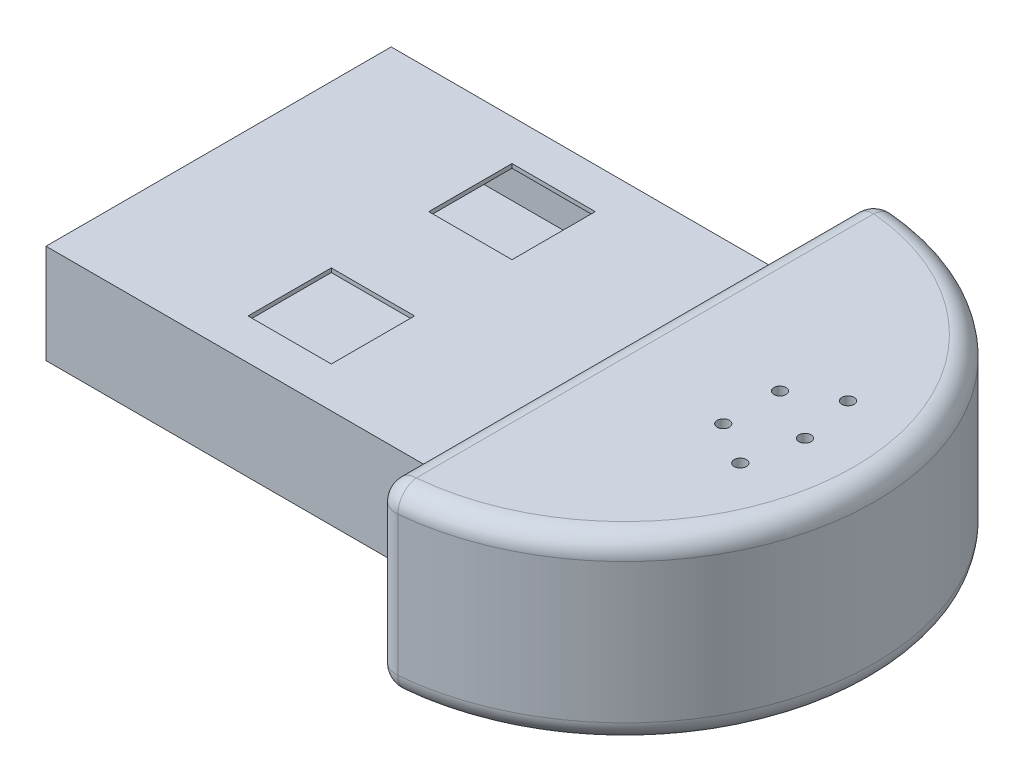
SolidWorks part; units mm, degrees
ref_plane "Front Plane" through (0, 0, 0) normal (0, 0, 1) x (1, 0, 0)
ref_plane "Top Plane" through (0, 0, 0) normal (0, 1, 0) x (1, 0, 0)
ref_plane "Right Plane" through (0, 0, 0) normal (1, 0, 0) x (0, 0, -1)
sketch "Sketch1" plane through (0, 0, 0) normal (0, 1, 0) x (1, 0, 0)
  line L0 (5, 6.1543) -> (5, 4.25)
  line L1 (-5, 4.25) -> (5, 4.25)
  line L2 (-5, 4.25) -> (-5, -4.25)
  line L3 (-5, -4.25) -> (5, -4.25)
  line L5 (-5, 4.25) -> (5, -4.25) construction
  line L6 (-5, -4.25) -> (5, 4.25) construction
  line L7 (5, -4.25) -> (5, -6.1543)
  arc A0 (5, -6.1543) -> (5, 6.1543) centre (5, 0) ccw
  point P0 (0, 0)
  dimension "D1" = 8.5
  dimension "D2" = 10
extrude "Boss-Extrude1" add sketch "Sketch1" along normal blind 2.44
sketch "Sketch2" plane through (0, 2.44, 0) normal (0, 1, 0) x (1, 0, 0)
  line L0 (5, 4.25) -> (5, -4.25) construction
  line L1 (5, 6.1543) -> (5, -6.1543)
  arc A0 (5, -6.1543) -> (5, 6.1543) centre (5, 0) ccw
extrude "Boss-Extrude2" add sketch "Sketch2" along normal blind 1
sketch "Sketch3" plane through (0, 0, 0) normal (0, -1, 0) x (1, 0, 0)
  line L0 (5, 6.1543) -> (5, -6.1543)
  arc A0 (5, -6.1543) -> (5, 6.1543) centre (5, 0) ccw
extrude "Boss-Extrude3" add sketch "Sketch3" along normal blind 1
sketch "Sketch4" plane through (-5, 0, 0) normal (-1, 0, 0) x (0, 0, 1)
  line L0 (0, 2.44) -> (0, 0) construction
  line L1 (-4.25, 2.44) -> (4.25, 2.44) construction
  line L2 (-4.25, 1.22) -> (4.25, 1.22) construction
  line L3 (-4.25, 2.44) -> (-4.25, 0) construction
  line L4 (4.25, 2.44) -> (4.25, 0) construction
  line L5 (-4.25, 2.44) -> (4.25, 2.44) construction
  line L6 (-4.15, 2.34) -> (4.15, 2.34)
  line L7 (-4.15, 2.34) -> (-4.15, 0.75)
  line L8 (-4.15, 0.75) -> (4.15, 0.75)
  line L9 (4.15, 2.34) -> (4.15, 0.75)
  line L10 (4.25, 0) -> (-4.25, 0) construction
  dimension "D1" = 0.1
  dimension "D2" = 0.1
  dimension "D3" = 0.1
  dimension "D4" = 0.75
extrude "Cut-Extrude1" cut sketch "Sketch4" against normal blind 10
fillet "Fillet1" radius 0.5 6 edges at (5, -1, 0) (5, 3.44, 0) (5, 1.22, 6.1543) (5, 1.22, -6.1543) (11.1543, -1, 0) (11.1543, 3.44, 0)
sketch "Sketch5" plane through (0, 3.44, 0) normal (0, 1, 0) x (1, 0, 0)
  line L0 (5.5, 5.6322) -> (5.5, -5.6322) construction
  line L1 (5.5, 0) -> (10.6543, 0) construction
  arc A0 (5.5, -5.6322) -> (5.5, 5.6322) centre (5, 0) ccw construction
  circle A1 centre (9.1722, 1.326) radius 0.15
  circle A2 centre (8.1255, 0.698) radius 0.15
  circle A3 centre (9.4397, 0) radius 0.15
  circle A4 centre (9.1722, -1.326) radius 0.15
  circle A5 centre (8.1255, -0.698) radius 0.15
  dimension "D1" = 0.3
extrude "Cut-Extrude2" cut sketch "Sketch5" against normal blind 0.5
sketch "Sketch6" plane through (0, 2.44, 0) normal (0, 1, 0) x (1, 0, 0)
  line L0 (-5, 0) -> (5, 0) construction
  line L1 (-5, 4.25) -> (-5, -4.25) construction
  line L2 (5, 4.25) -> (5, -4.25) construction
  line L3 (0, 4.25) -> (0, -4.25) construction
  line L4 (5, 4.25) -> (-5, 4.25) construction
  line L5 (-5, -4.25) -> (5, -4.25) construction
  line L6 (-1.025, -3.25) -> (1.025, -3.25)
  line L7 (-1.025, 3.25) -> (1.025, 3.25)
  line L8 (-1.025, 3.25) -> (-1.025, 1.2)
  line L9 (-1.025, 1.2) -> (1.025, 1.2)
  line L10 (1.025, 3.25) -> (1.025, 1.2)
  line L11 (-1.025, 3.25) -> (1.025, 1.2) construction
  line L12 (-1.025, 1.2) -> (1.025, 3.25) construction
  line L13 (-1.025, -3.25) -> (-1.025, -1.2)
  line L14 (-1.025, -1.2) -> (1.025, -1.2)
  line L15 (1.025, -3.25) -> (1.025, -1.2)
  point P12 (0, 2.225)
  dimension "D1" = 1
  dimension "D2" = 2.05
  dimension "D3" = 2.05
extrude "Cut-Extrude3" cut sketch "Sketch6" against normal blind 0.5
